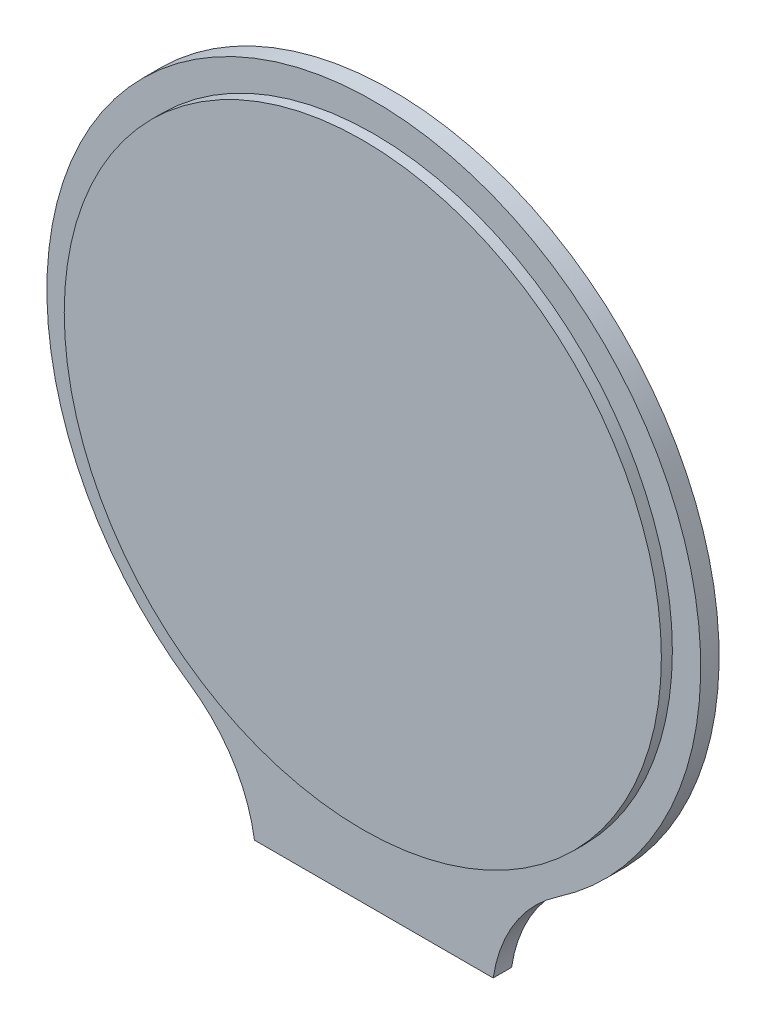
SolidWorks part; units mm, degrees
ref_plane "Plan de face" through (0, 0, 0) normal (0, 0, 1) x (1, 0, 0)
ref_plane "Plan de dessus" through (0, 0, 0) normal (0, 1, 0) x (1, 0, 0)
ref_plane "Plan de droite" through (0, 0, 0) normal (1, 0, 0) x (0, 0, -1)
sketch "Contour_Écran" plane through (0, 0, 0) normal (0, 0, 1) x (1, 0, 0)
  line L0 (10.0051, 0) -> (10.0051, -22.8841) construction
  line L5 (0, 0) -> (10.0051, 0) construction
  line L6 (0, 0) -> (-10.0051, 0) construction
  line L7 (-10.0051, 0) -> (-10.0051, -22.8841) construction
  line L8 (-6.5, -20.3) -> (6.5, -20.3) construction
  line L9 (0, 0) -> (-10.0051, -14.722) construction
  line L10 (0, 0) -> (10.0051, -14.722) construction
  line L11 (-6.5, -20.3) -> (6.5, -20.3)
  line L12 (0, 0) -> (-6.5, -20.3) construction
  line L13 (0, 0) -> (6.5, -20.3) construction
  arc A0 (10.0051, -14.722) -> (-10.0051, -14.722) centre (0, 0) ccw
  arc A1 (-10.0051, -14.722) -> (-6.5, -20.3) centre (-14.6194, -21.5118) cw
  arc A2 (10.0051, -14.722) -> (6.5, -20.3) centre (14.6194, -21.5118) ccw
  point P4 (0, -20.3)
  dimension "D1" = 17.8
  dimension "D2" = 13
  dimension "D3" = 20.3
  dimension "D4" = 55.8
  dimension "D5" = 55.8
extrude "Boss.-Extru.1_Contour_Écran" add sketch "Contour_Écran" along normal blind 1
sketch "Écran" plane through (0, 0, 1) normal (0, 0, 1) x (1, 0, 0)
  circle A0 centre (0, 0) radius 16.256
  dimension "D1" = 32.512
extrude "Boss.-Extru.1_Écran" add sketch "Écran" along normal blind 0.6
